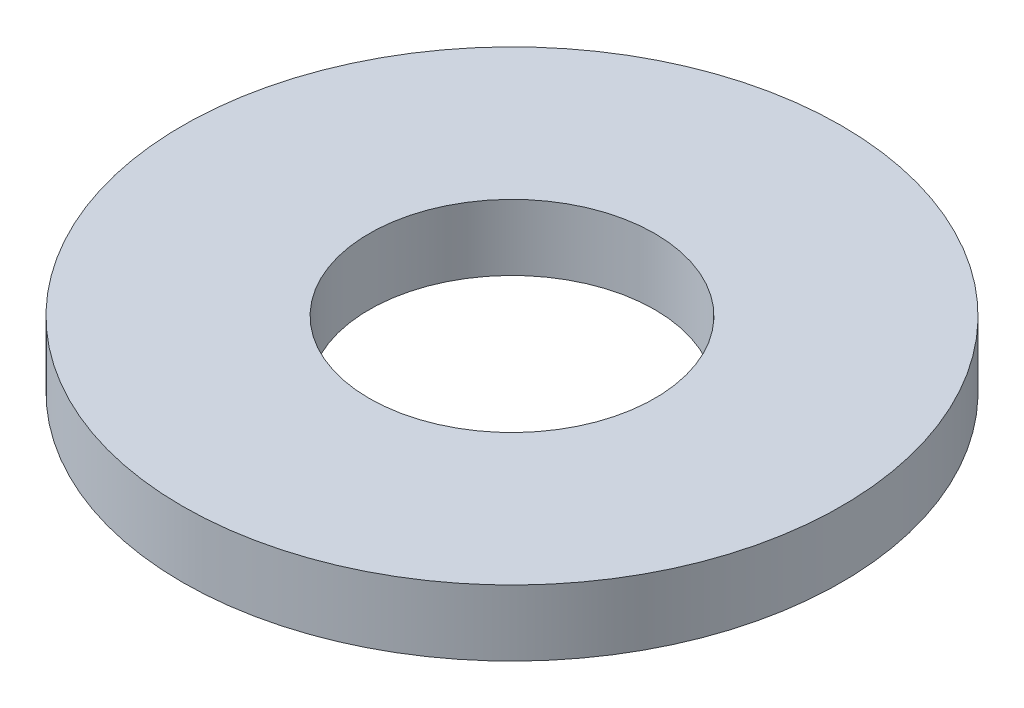
SolidWorks part; units mm, degrees
material "AISI 1020"
ref_plane "Спереди" through (0, 0, 0) normal (0, 0, 1) x (1, 0, 0)
ref_plane "Сверху" through (0, 0, 0) normal (0, 1, 0) x (1, 0, 0)
ref_plane "Справа" through (0, 0, 0) normal (1, 0, 0) x (0, 0, -1)
sketch "Эскиз1" plane through (0, 0, 0) normal (0, 1, 0) x (1, 0, 0)
  circle A0 centre (0, 0) radius 6.5
  circle A1 centre (0, 0) radius 15
  dimension "D1" = 30
  dimension "D2" = 13
extrude "Бобышка-Вытянуть1" add sketch "Эскиз1" along normal blind 3
